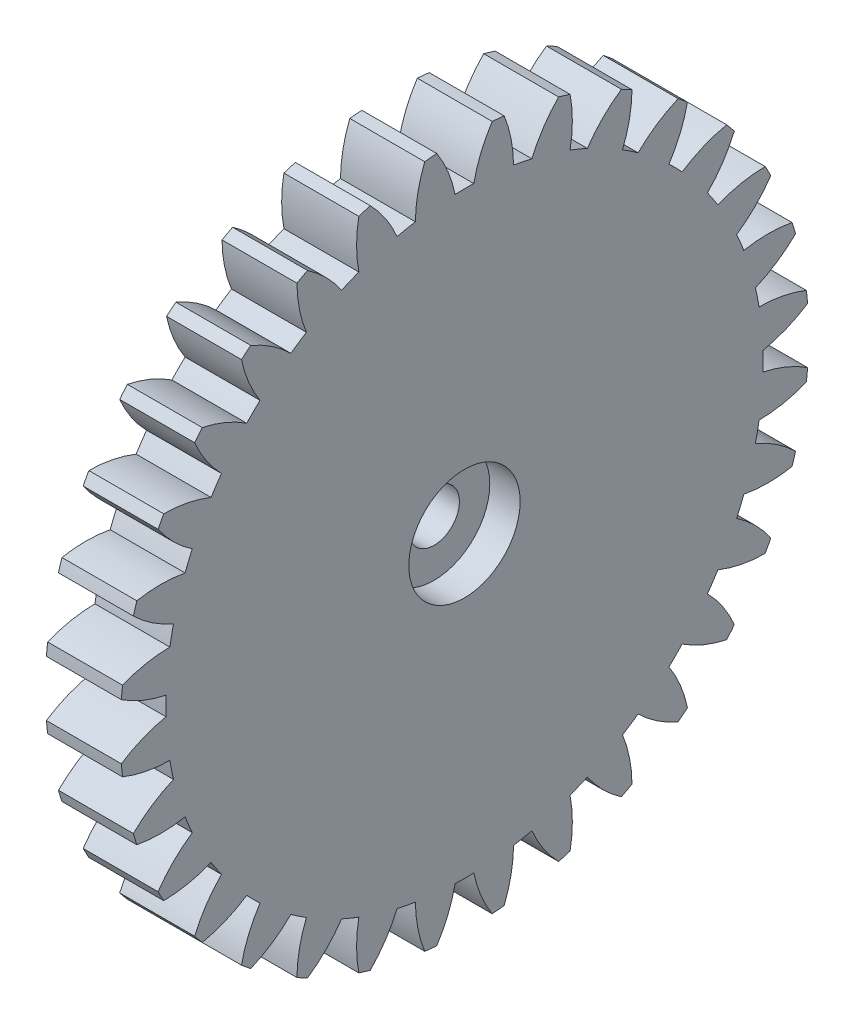
SolidWorks part; units mm, degrees
ref_plane "Plane1" through (0, 0, 0) normal (0, 0, 1) x (1, 0, 0)
ref_plane "Plane2" through (0, 0, 0) normal (0, 1, 0) x (1, 0, 0)
ref_plane "Plane3" through (0, 0, 0) normal (1, 0, 0) x (0, 0, -1)
sketch "HoldingSke" plane through (0, 0, 0) normal (0, 1, 0) x (1, 0, 0)
  line L0 (0, 0) -> (0.848, -0.5299)
  line L1 (-15, 0) -> (100, 0) construction
  line L2 (0, 0) -> (-2.1039, 2.3779)
  line L3 (0, 0) -> (-11.863, 4.5341)
  line L4 (0, 0) -> (7.3237, 4.5764)
  line L5 (0, 0) -> (-46.8476, -17.4728)
  line L6 (0, 0) -> (-3.0672, -2.0694)
  line L7 (-2.1039, 2.3779) -> (8.6586, 51.2059)
  line L8 (-76.2, 54.61) -> (-75.9, 54.61)
  line L9 (-71.009, 38.7566) -> (-53.1078, 45.2721)
  line L10 (-76.2, 71.12) -> (104.1128, 71.12)
  line L11 (0, 0) -> (-3.7, 0)
  line L12 (-76.2, 101.6) -> (-76.162, 101.6)
  line L13 (24.9733, 27.94) -> (52.9518, 28.4284)
  line L14 (24.9733, 27.94) -> (24.9743, 27.94)
  line L15 (24.9733, 27.94) -> (100.4006, 29.5858)
  line L16 (-63.627, -1) -> (-12.827, -1)
  circle A0 centre (0, 0) radius 1
  circle A1 centre (0, 0) radius 14.749
  circle A2 centre (0, 0) radius 37.5
  circle A3 centre (0, 0) radius 1.25
  dimension "MHD" = 29.498
  dimension "Hub_dia" = 75
  dimension "Bore" = 2
  dimension "MBD" = 2.5
  dimension "Num_teeth" = 32
  dimension "Pitch" = 1
  dimension "Overall_len" = 50
  dimension "Show_teeth" = 32
  dimension "Thickness" = 3.7
  dimension "OAL" = 50.0001
  dimension "T_dim" = 0.3
  dimension "Ap" = 20
  dimension "H" = 19.05
  dimension "Pitch_radius" = 180.3128
  dimension "Width" = 3.7
  dimension "Backlash" = 0.038
  dimension "Addendum_fac" = 1
  dimension "Dedendum_fac" = 1.25
  dimension "Clearance_fac" = 0.25
  dimension "Dedendum_add" = 0.001
  dimension "Module" = 1
sketch "BasProSke" plane through (0, 0, 0) normal (0, 1, 0) x (1, 0, 0)
  line L0 (-10, 0) -> (60, 0) construction
  line L1 (0, 0) -> (0, 17)
  line L2 (0, 0) -> (3.7, 0)
  line L3 (3.7, 0) -> (3.7, 17)
  line L4 (3.7, 17) -> (0, 17)
  dimension "Thickness" = 3.7
  dimension "Diameter" = 34
revolve "Base-Revolve" add sketch "BasProSke" angle 360 about L0
sketch "TooCutSke" plane through (0, 0, 0) normal (1, 0, 0) x (0, 0, -1)
  line L1 (0, 0) -> (0, 107) construction
  line L2 (0, 0) -> (-0.8516, 15.9773) construction
  line L3 (0, 0) -> (-3.1334, 31.8138) construction
  line L4 (-0.8516, 15.9773) -> (-1.5667, 15.9069) construction
  arc A0 (0.462, 14.7418) -> (-0.462, 14.7418) centre (0, 0) ccw
  arc A1 (1.3867, 16.9688) -> (-1.3867, 16.9688) centre (0, 0) ccw
  circle A2 centre (0, 0) radius 16 construction
  circle A3 centre (0, 0) radius 15.0351 construction
  arc A4 (-0.462, 14.7418) -> (-1.3867, 16.9688) centre (-6.7293, 13.4451) ccw
  arc A5 (1.3867, 16.9688) -> (0.462, 14.7418) centre (6.7293, 13.4451) ccw
  dimension "Root_dia" = 29.498
  dimension "Overcut_dia" = 34.0508
  dimension "Pitch_dia" = 32
  dimension "Base_dia" = 30.0702
  dimension "Flank_rad" = 6.4
  dimension "Half_ang" = 5.625
  dimension "Half_CT" = 0.7186
extrude "ToothCut" cut sketch "TooCutSke" along normal through all
fillet "Breaks" [suppressed] radius 0.02
fillet "RootFillets" [suppressed] radius 0.251
pattern_circular "TeethCuts" count 32 every 11.25 about axis through (-10, 0, 0) along (1, 0, 0) of "ToothCut", "RootFillets", "Breaks"
sketch "HubNeaOneSke" plane through (0, 0, 0) normal (-1, 0, 0) x (0, 0, 1)
  circle A0 centre (0, 0) radius 14.749
  dimension "Diameter" = 29.498
extrude "HubNearOne" [suppressed] add sketch "HubNeaOneSke" along normal blind 46.3001
sketch "HubNeaBotSke" plane through (0, 0, 0) normal (-1, 0, 0) x (0, 0, 1)
  circle A0 centre (0, 0) radius 14.749
  dimension "Diameter" = 29.498
extrude "HubNearBoth" [suppressed] add sketch "HubNeaBotSke" along normal blind 23.1501
ref_plane "FarPln" through (3.7, 0, 0) normal (1, 0, 0) x (0, 0, -1)
sketch "HubFarSke" plane through (3.7, 0, 0) normal (1, 0, 0) x (0, 0, -1)
  circle A0 centre (0, 0) radius 14.749
  dimension "Diameter" = 29.498
extrude "HubFar" [suppressed] add sketch "HubFarSke" along normal blind 23.1501
sketch "BorSke" plane through (0, 0, 0) normal (1, 0, 0) x (0, 0, -1)
  circle A0 centre (0, 0) radius 1.25
  dimension "Diameter" = 2.5
extrude "Bore" cut sketch "BorSke" along normal mid plane 100.0002
sketch "KeySke" plane through (0, 0, 0) normal (1, 0, 0) x (0, 0, -1)
  line L0 (-0.4, 0) -> (-0.4, 1.55)
  line L1 (-0.4, 1.55) -> (0.4, 1.55)
  line L2 (0.4, 1.55) -> (0.4, 0)
  line L3 (0, 0) -> (0, 34) construction
  line L4 (-0.4, 0) -> (0.4, 0)
  dimension "Offset" = 1.55
  dimension "Width" = 0.8
extrude "Keyway" [suppressed] cut sketch "KeySke" along normal mid plane 100.0002
pattern_circular "Keyway2" [suppressed] count 2 every 90 about axis through (-10, 0, 0) along (1, 0, 0)
extrude "Cut-Extrude5" cut sketch "Sketch5" against normal blind 3.7
sketch "Sketch5" plane through (3.7, -115.3943, -107.0569) normal (1, 0, 0) x (0, 0, -1)
  circle A0 centre (-107.057, 115.3942) radius 1.25
  point P3 (257.8573, 53.7538)
extrude "Cut-Extrude6" cut sketch "Sketch6" against normal blind 1.5
sketch "Sketch6" plane through (3.7, -115.3943, -107.0569) normal (1, 0, 0) x (0, 0, -1)
  circle A0 centre (256.7004, 54.6182) radius 2.75
  circle A2 centre (-107.057, 115.3942) radius 2.75
sketch "Sketch7" plane through (3.7, 0, 0) normal (1, 0, 0) x (0, 0, -1)
  circle A0 centre (0, 0) radius 2.75
  dimension "D1" = 5.5
extrude "Cut-Extrude7" cut sketch "Sketch7" against normal blind 1.5
equation "' \"Module@HoldingSke\" = 6.35"
equation "' \"Num_teeth@HoldingSke\" = 12"
equation "' \"Ap@HoldingSke\" =  20"
equation "' \"Ap@HoldingSke\" = 20"
equation "' \"Width@HoldingSke\" = 0.5 * 25.4"
equation "' \"Hub_dia@HoldingSke\"= 1 * 25.4"
equation "' \"Hub_dia@HoldingSke\" = 1 * 25.4"
equation "' \"Overall_len@HoldingSke\" = 1.0 * 25.4"
equation "' \"Bore@HoldingSke\" = 0.75 * 25.4"
equation "' \"T_dim@HoldingSke\" = 0.1 * 25.4"
equation "' \"Width@KeySke\" = 0.25 * 25.4"
equation "' \"Show_teeth@HoldingSke\" = 13"
equation "' \"Backlash@HoldingSke\" = 0.009 * 25.4"
equation "' \"Addendum_fac@HoldingSke\" = 1.0"
equation "' \"Dedendum_fac@HoldingSke\" = 1.25"
equation "' \"Dedendum_add@HoldingSke\" = 0.00005 * 25.4"
equation "' \"Clearance_fac@HoldingSke\" = 0.25"
equation "\"Pitch@HoldingSke\" = 1 / \"Module@HoldingSke\""
equation "\"Overcut_dia@TooCutSke\" = (\"Num_teeth@HoldingSke\" + 2 * \"Addendum_fac@HoldingSke\") / \"Pitch@HoldingSke\" + 0.002 * 25.4"
equation "\"Pitch_dia@TooCutSke\" = \"Num_teeth@HoldingSke\" / \"Pitch@HoldingSke\""
equation "\"Base_dia@TooCutSke\" = \"Num_teeth@HoldingSke\" / \"Pitch@HoldingSke\" * cos((\"Ap@HoldingSke\"  * 3.14159265 / 180))"
equation "\"Root_dia@TooCutSke\" = (\"Num_teeth@HoldingSke\" + 2) / \"Pitch@HoldingSke\" - 2 * (\"Addendum_fac@HoldingSke\" + \"Dedendum_fac@HoldingSke\") / \"Pitch@HoldingSke\" - \"Dedendum_add@HoldingSke\" * 2"
equation "\"Half_ang@TooCutSke\" = 180 / \"Num_teeth@HoldingSke\""
equation "\"Half_CT@TooCutSke\" = \"Num_teeth@HoldingSke\" / \"Pitch@HoldingSke\" * sin((3.14159265 / 2 / \"Num_teeth@HoldingSke\")) / 2 - 7 * \"Backlash@HoldingSke\" / 4"
equation "\"Flank_rad@TooCutSke\" = \"Num_teeth@HoldingSke\" / \"Pitch@HoldingSke\" / 5"
equation "\"Radius@RootFillets\" = \"Clearance_fac@HoldingSke\" / \"Pitch@HoldingSke\" + \"Dedendum_add@HoldingSke\""
equation "\"Break_rad@Breaks\" = 0.02 / \"Pitch@HoldingSke\""
equation "\"Thickness@HoldingSke\" = \"Width@HoldingSke\""
equation "\"OAL@HoldingSke\" = \"Thickness@HoldingSke\""
equation "\"MHD@HoldingSke\" = (\"Num_teeth@HoldingSke\" + 2) / \"Pitch@HoldingSke\" - 2 * (\"Addendum_fac@HoldingSke\" + \"Dedendum_fac@HoldingSke\")  / \"Pitch@HoldingSke\" - \"Dedendum_add@HoldingSke\" * 2"
equation "\"MBD@HoldingSke\" = (\"Num_teeth@HoldingSke\" + 2) / \"Pitch@HoldingSke\" - 2 * (\"Addendum_fac@HoldingSke\" + \"Dedendum_fac@HoldingSke\")  / \"Pitch@HoldingSke\" - \"Dedendum_add@HoldingSke\" * 2 - 0.002 * 25.4"
equation "\"MHD@HoldingSke\" = ((sgn( \"MHD@HoldingSke\" - \"Hub_dia@HoldingSke\" )-1)*( \"MHD@HoldingSke\" - \"Hub_dia@HoldingSke\" ))/-2+ \"Hub_dia@HoldingSke\""
equation "\"MBD@HoldingSke\"= 2.5mm"
equation "\"OAL@HoldingSke\" = ((sgn( \"OAL@HoldingSke\" - \"Overall_len@HoldingSke\" )+1)*( \"OAL@HoldingSke\" - \"Overall_len@HoldingSke\" ))/2 + \"Overall_len@HoldingSke\" + 0.000002 * 25.4"
equation "\"Num_teeth@TeethCuts\" = int( \"Show_teeth@HoldingSke\" ) + 1"
equation "\"Num_teeth@TeethCuts\" = ((sgn( \"Num_teeth@TeethCuts\" - \"Num_teeth@HoldingSke\" )-1)*( \"Num_teeth@TeethCuts\" - \"Num_teeth@HoldingSke\" ))/-2+ \"Num_teeth@HoldingSke\""
equation "\"Num_teeth@TeethCuts\" = ((sgn( \"Num_teeth@TeethCuts\" - 2.0)+1)*( \"Num_teeth@TeethCuts\" - 2.0))/2 +2.0"
equation "\"Angle@TeethCuts\" = 360.0 / \"Num_teeth@HoldingSke\""
equation "\"Diameter@BasProSke\" = (\"Num_teeth@HoldingSke\" + 2 * \"Addendum_fac@HoldingSke\") / \"Pitch@HoldingSke\""
equation "\"Thickness@BasProSke\"  = \"Thickness@HoldingSke\""
equation "' \"Fillet_rad@BasProSke\" =  \"Thickness@HoldingSke\" * 0.05"
equation "' \"Fillet_rad@BasProSke\" = \"Thickness@HoldingSke\" * 0.05"
equation "\"MHD@HoldingSke\" = ((sgn( \"MHD@HoldingSke\" - \"Root_dia@TooCutSke\" )-1)*( \"MHD@HoldingSke\" - \"Root_dia@TooCutSke\" ))/-2+ \"Root_dia@TooCutSke\""
equation "\"Diameter@HubNeaOneSke\" = \"MHD@HoldingSke\""
equation "\"Length@HubNearOne\" = \"OAL@HoldingSke\" - \"Thickness@BasProSke\""
equation "\"Diameter@HubNeaBotSke\" = \"MHD@HoldingSke\""
equation "\"Length@HubNearBoth\" = ( \"OAL@HoldingSke\" - \"Thickness@BasProSke\" ) / 2.0"
equation "\"Thickness@FarPln\" = \"Thickness@BasProSke\""
equation "\"Diameter@HubFarSke\" = \"MHD@HoldingSke\""
equation "\"Length@HubFar\" = ( \"OAL@HoldingSke\" - \"Thickness@BasProSke\" ) / 2.0"
equation "\"Diameter@BorSke\" = \"MBD@HoldingSke\""
equation "\"D1@Bore\" = \"OAL@HoldingSke\" * 2.0"
equation "\"D1@Keyway\" = \"OAL@HoldingSke\" * 2.0"
equation "\"Offset@KeySke\" = \"T_dim@HoldingSke\" + \"MBD@HoldingSke\" / 2.0"
